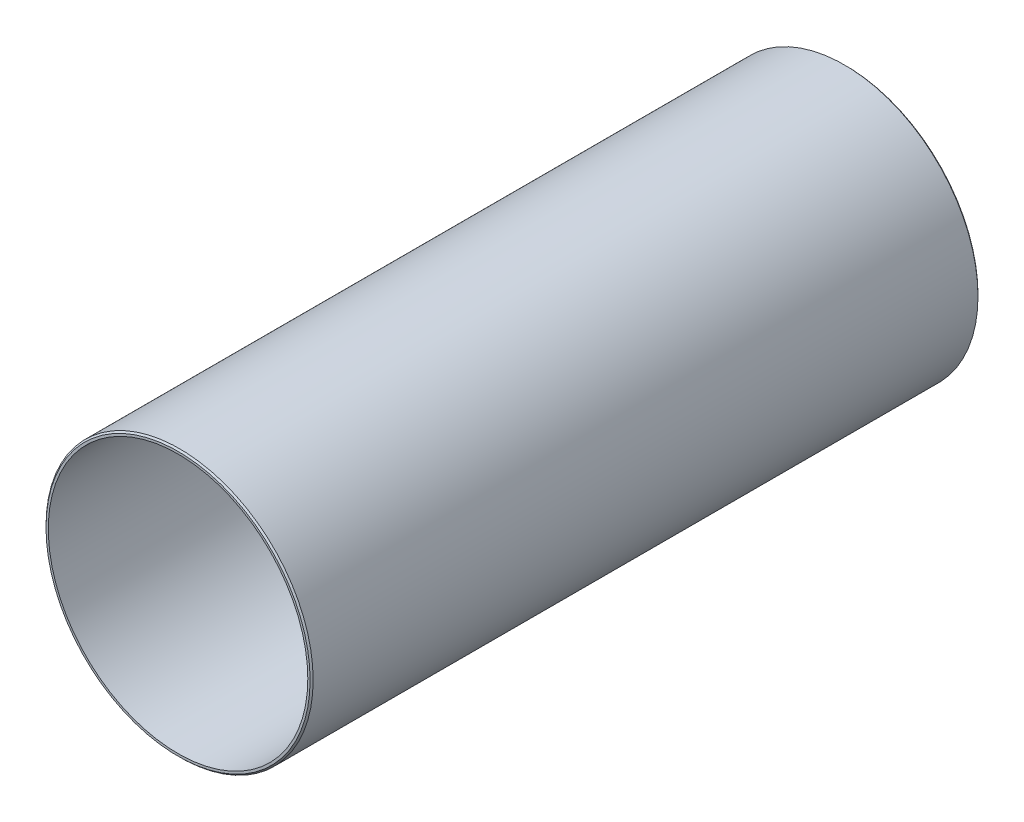
SolidWorks part; units mm, degrees
ref_plane "Front Plane" through (0, 0, 0) normal (0, 0, 1) x (1, 0, 0)
ref_plane "Top Plane" through (0, 0, 0) normal (0, 1, 0) x (1, 0, 0)
ref_plane "Right Plane" through (0, 0, 0) normal (1, 0, 0) x (0, 0, -1)
sketch "Sketch1" plane through (0, 0, 0) normal (0, 0, 1) x (1, 0, 0)
  circle A0 centre (0, 0) radius 17.5
  circle A1 centre (0, 0) radius 17
  dimension "D1" = 34
  dimension "D2" = 35
extrude "Boss-Extrude1" add sketch "Sketch1" against normal blind 87.5
chamfer "Chamfer1" distance 0.2 angle 45 2 edges at (17.5, 0, 0) (17.5, 0, -87.5)
